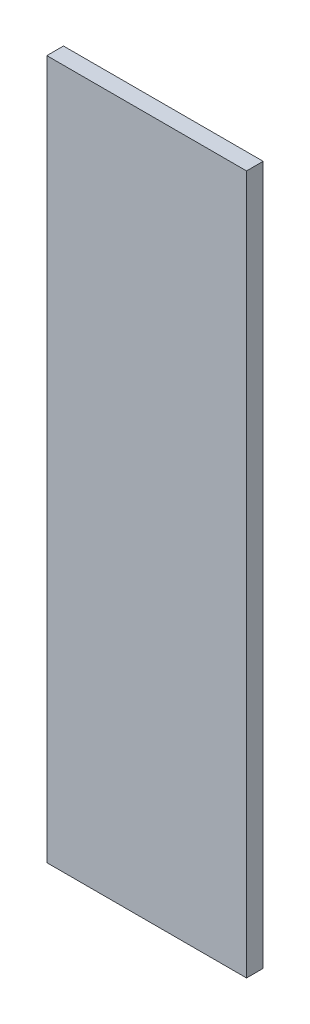
SolidWorks part; units mm, degrees
ref_plane "Płaszczyzna przednia" through (0, 0, 0) normal (0, 0, 1) x (1, 0, 0)
ref_plane "Płaszczyzna górna" through (0, 0, 0) normal (0, 1, 0) x (1, 0, 0)
ref_plane "Płaszczyzna prawa" through (0, 0, 0) normal (1, 0, 0) x (0, 0, -1)
sketch "Sketch1" plane through (0, 0, 0) normal (0, 0, 1) x (1, 0, 0)
  line L1 (-6, 21) -> (6, 21)
  line L2 (-6, 21) -> (-6, -21)
  line L3 (-6, -21) -> (6, -21)
  line L4 (6, 21) -> (6, -21)
  line L5 (-6, 21) -> (6, -21) construction
  line L6 (-6, -21) -> (6, 21) construction
  point P0 (0, 0)
  dimension "D1" = 12
  dimension "D2" = 42
extrude "Boss-Extrude1" add sketch "Sketch1" along normal blind 1
